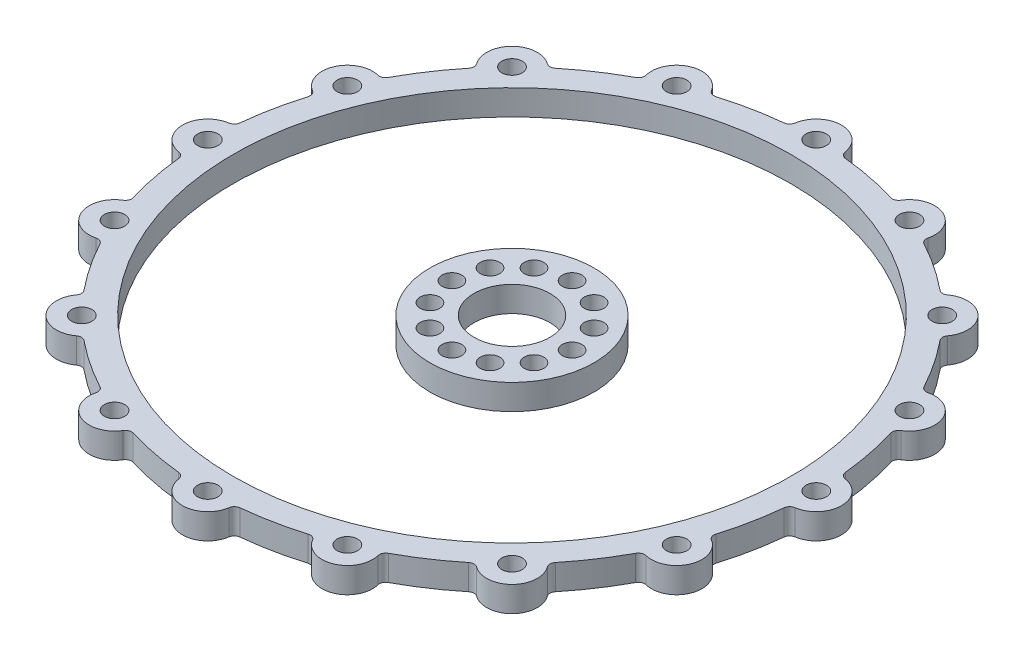
SolidWorks part; units mm, degrees
ref_plane "Front Plane" through (0, 0, 0) normal (0, 0, 1) x (1, 0, 0)
ref_plane "Top Plane" through (0, 0, 0) normal (0, 1, 0) x (1, 0, 0)
ref_plane "Right Plane" through (0, 0, 0) normal (1, 0, 0) x (0, 0, -1)
sketch "Sketch1" plane through (0, 0, 0) normal (0, 1, 0) x (1, 0, 0)
  circle A0 centre (0, 0) radius 76.2
  circle A1 centre (0, 0) radius 9.525
  dimension "D1" = 152.4
  dimension "D2" = 19.05
extrude "Boss-Extrude1" add sketch "Sketch1" along normal blind 6.35
sketch "Sketch2" plane through (0, 6.35, 0) normal (0, 1, 0) x (1, 0, 0)
  circle A0 centre (0, 0) radius 76.2 construction
  arc A1 (6.3445, 75.9354) -> (-6.3445, 75.9354) centre (0, 0) ccw
  arc A2 (6.3445, 75.9354) -> (-6.3445, 75.9354) centre (0, 76.2) ccw
  dimension "D1" = 12.7
extrude "Boss-Extrude3" add sketch "Sketch2" against normal through all
fillet "Fillet1" radius 1.5875 2 edges at (6.3445, 3.175, -75.9354) (-6.3445, 3.175, -75.9354)
hole_wizard "#10 Clearance Hole1" positions "Sketch3" profile "Sketch5" hole size "#10" standard "ANSI Inch"
sketch "Sketch3" plane through (0, 6.35, 0) normal (0, 1, 0) x (1, 0, 0)
  circle A0 centre (0, 0) radius 76.2 construction
  point P4 (0, 76.2)
  dimension "D1" = 152.4
sketch "Sketch5" plane through (0, 6.35, -76.2) normal (1, 0, 0) x (0, 0, 1)
  line L0 (0, 0) -> (0, 8.1378)
  line L1 (0, 8.1378) -> (2.5527, 6.604)
  line L2 (2.5527, 6.604) -> (2.5527, 0)
  line L5 (2.5527, 0) -> (0, 0)
  line L10 (0, 8.1378) -> (-2.5527, 6.604) construction
  line L11 (0, -6.35) -> (0, 107.95) construction
  dimension "Hole Dia." = 5.1054
  dimension "Hole Depth" = 6.604
  dimension "Drill Angle" = 118
pattern_circular "CirPattern1" count 16 over 360 about axis through (0, 0, 0) along (0, 1, 0) of "Boss-Extrude3", "Fillet1", "#10 Clearance Hole1"
hole_wizard "#10 (0.1935) Diameter Hole1" positions "Sketch6" profile "Sketch7" hole size "#10" standard "ANSI Inch"
sketch "Sketch6" plane through (0, 6.35, 0) normal (0, 1, 0) x (1, 0, 0)
  circle A0 centre (0, 0) radius 15.0495
  point P5 (0, 15.0495)
  dimension "D1" = 30.099
sketch "Sketch7" plane through (0, 6.35, -15.0495) normal (1, 0, 0) x (0, 0, 1)
  line L0 (0, 0) -> (0, 13.4146)
  line L1 (0, 13.4146) -> (2.4574, 11.938)
  line L2 (2.4574, 11.938) -> (2.4574, 0)
  line L5 (2.4574, 0) -> (0, 0)
  line L10 (0, 13.4146) -> (-2.4575, 11.938) construction
  line L11 (0, -6.35) -> (0, 107.95) construction
  dimension "Hole Dia." = 4.9149
  dimension "Hole Depth" = 11.938
  dimension "Drill Angle" = 118
pattern_circular "CirPattern2" count 12 over 360 about axis through (0, 0, 0) along (0, 1, 0) of "#10 (0.1935) Diameter Hole1"
sketch "Sketch8" plane through (0, 6.35, 0) normal (0, 1, 0) x (1, 0, 0)
  line L0 (0, 9.525) -> (0, 15.0495) construction
  line L1 (0, 15.0495) -> (0, 20.574) construction
  line L2 (0, 20.574) -> (0, 69.85) construction
  line L3 (17.8176, -10.287) -> (60.4919, -34.925) construction
  line L4 (0, 55.0158) -> (0, 26.924)
  line L5 (15.5136, 52.7832) -> (8.7884, 29.9014)
  line L6 (17.0132, 26.1128) -> (30.0325, 46.0954)
  line L7 (41.8119, 35.7561) -> (23.6862, 20.2556)
  line L8 (28.5094, 12.5914) -> (50.3259, 22.2269)
  line L9 (54.5513, 7.1338) -> (30.903, 4.0413)
  line L10 (30.7603, -5.0131) -> (68.9404, -11.2355)
  line L11 (25.8551, 7.5111) -> (29.9288, 8.6945) construction
  line L12 (54.9463, 2.7641) -> (59.183, 2.9772) construction
  line L13 (59.183, 2.9772) -> (63.4198, 3.1903) construction
  line L14 (17.8499, 20.1565) -> (13.64, 15.4026) construction
  line L15 (54.2448, 33.0114) -> (59.6693, 36.3126) construction
  line L16 (0, 26.924) -> (0, 20.574)
  line L17 (0, 20.574) -> (0, 19.5016)
  circle A0 centre (0, 0) radius 69.85 construction
  arc A1 (6.2782, 77.1525) -> (-6.2782, 77.1525) centre (0, 76.2) ccw construction
  arc A2 (6.2782, 77.1525) -> (-6.2782, 77.1525) centre (0, 76.2) ccw construction
  arc A3 (-6.2782, 77.1525) -> (6.2782, 77.1525) centre (0, 76.2) ccw construction
  arc A4 (6.2782, 77.1525) -> (7.6875, 75.8112) centre (7.8477, 77.3906) ccw construction
  circle A5 centre (0, 0) radius 9.525 construction
  circle A6 centre (0, 0) radius 20.574 construction
  circle A7 centre (0, 0) radius 55.0158 construction
  arc A8 (15.5136, 52.7832) -> (0, 55.0158) centre (7.9174, 55.0158) ccw
  arc A9 (8.7884, 29.9014) -> (17.0132, 26.1128) centre (13.179, 28.6109) ccw
  arc A10 (30.0325, 46.0954) -> (41.8119, 35.7561) centre (36.6662, 41.7733) cw
  arc A11 (28.5094, 12.5914) -> (23.6862, 20.2556) centre (26.6605, 16.7776) cw
  arc A12 (54.5513, 7.1338) -> (50.3259, 22.2269) centre (53.5247, 14.9844) ccw
  arc A13 (30.903, 4.0413) -> (30.7603, -5.0131) centre (31.4964, -0.4964) ccw
  circle A14 centre (0, 0) radius 26.924 construction
  circle A15 centre (0, 0) radius 31.1661 construction
  circle A16 centre (0, 0) radius 63.5 construction
  dimension "D4" = 6.35
  dimension "D1" = 120
sketch "Sketch9" plane through (0, 6.35, 0) normal (0, 1, 0) x (1, 0, 0)
  circle A0 centre (0, 0) radius 69.85
  circle A1 centre (0, 0) radius 20.574
extrude "Cut-Extrude1" cut sketch "Sketch9" against normal through all
sketch "Sketch12" plane through (0, 6.35, 0) normal (0, 1, 0) x (1, 0, 0)
  line L2 (20.574, 0) -> (42.926, 0) construction
  line L3 (42.926, 0) -> (48.5834, 23.4418) construction
  line L4 (48.5834, 23.4418) -> (38.1661, 38.1661) construction
  line L5 (38.1661, 38.1661) -> (27.7488, 52.8903) construction
  line L6 (27.7488, 52.8903) -> (1.2567, 58.897) construction
  line L7 (1.2567, 58.897) -> (-17.3746, 47.7364) construction
  line L8 (42.926, 0) -> (32.5087, 14.7242) construction
  line L9 (47.1981, -180.1465) -> (-7.2452, -802.4361) construction
  line L10 (32.5087, 14.7242) -> (22.0913, 29.4485) construction
  line L11 (22.0913, 29.4485) -> (11.674, 44.1727) construction
  line L12 (11.674, 44.1727) -> (1.2567, 58.897) construction
  line L13 (38.1661, 38.1661) -> (0, 0) construction
  line L14 (0, 0) -> (-17.3746, 47.7364) construction
  line L15 (-1000, 0) -> (49000, 0) construction
  line L19 (-68.7888, 12.1293) -> (-46.7764, 8.2479) construction
  line L20 (-46.7764, 8.2479) -> (-36.0059, 36.5758) construction
  line L21 (-36.0059, 36.5758) -> (-17.3746, 47.7364) construction
  line L22 (27.7488, 52.8903) -> (9.1175, 41.7297) construction
  line L23 (9.1175, 41.7297) -> (-9.5138, 30.5691) construction
  line L24 (-9.5138, 30.5691) -> (-28.1451, 19.4085) construction
  line L26 (-28.1451, 19.4085) -> (-46.7764, 8.2479) construction
  circle A3 centre (0, 0) radius 20.574 construction
  circle A4 centre (0, 0) radius 69.85 construction
  spline S0 degree 3 poles (20.574, 0) (42.926, 0) (48.5834, 23.4418) (38.1661, 38.1661) knots 0 0 0 0 1 1 1 1
  spline S1 degree 3 poles (38.1661, 38.1661) (27.7488, 52.8903) (1.2567, 58.897) (-17.3746, 47.7364) knots 0 0 0 0 1 1 1 1
  spline S2 degree 3 poles (-68.7888, 12.1293) (-46.7764, 8.2479) (-36.0059, 36.5758) (-17.3746, 47.7364) knots 0 0 0 0 1 1 1 1
  point P14 (-52.9496, 9.3364)
  point P21 (37.8529, 0)
  dimension "D1" = 53.975
  dimension "D2" = 50.8
  dimension "D3" = 45
  dimension "D4" = 110
  dimension "D5" = 10
  dimension "D6" = 22.352
